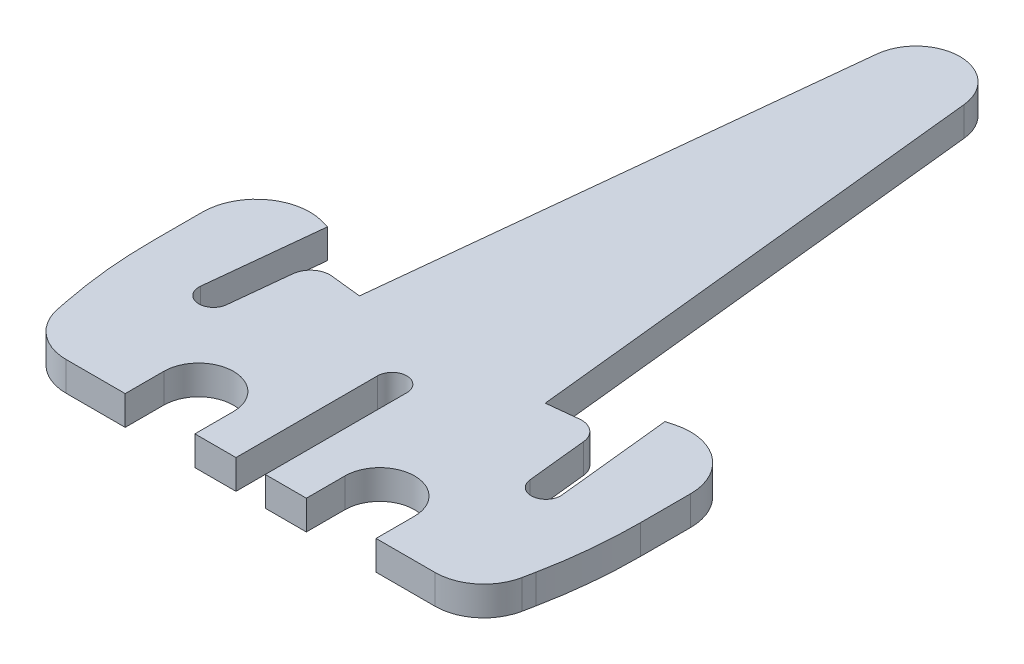
SolidWorks part; units mm, degrees
ref_plane "Front Plane" through (0, 0, 0) normal (0, 0, 1) x (1, 0, 0)
ref_plane "Top Plane" through (0, 0, 0) normal (0, 1, 0) x (1, 0, 0)
ref_plane "Right Plane" through (0, 0, 0) normal (1, 0, 0) x (0, 0, -1)
sketch "Sketch1" plane through (0, 0, 0) normal (0, 1, 0) x (1, 0, 0)
  line L0 (4.4753, 54.1404) -> (9.5172, 6.17)
  line L1 (9.5172, 6.17) -> (12.6862, 6.5137)
  line L2 (14.8909, 4.7344) -> (15.5383, -1.425)
  line L3 (18.5218, -1.1114) -> (17.2833, 10.6723)
  line L4 (17.2833, 10.6723) -> (18.0765, 10.8849)
  line L5 (25, -14.5) -> (25, 5.5723)
  line L6 (25, -14.5) -> (12.85, -14.5) construction
  line L7 (12.85, -14.5) -> (12.85, -10.55)
  line L8 (5.71, -10.55) -> (5.71, -14.5)
  line L9 (5.71, -14.5) -> (1.5, -14.5)
  line L10 (1.5, -14.5) -> (1.5, 0)
  line L11 (-1.5, 0) -> (-1.5, -14.5)
  line L12 (-1.5, -14.5) -> (-5.71, -14.5)
  line L13 (-5.71, -14.5) -> (-5.71, -10.55)
  line L14 (-12.85, -10.55) -> (-12.85, -14.5)
  line L15 (-12.85, -14.5) -> (-25, -14.5) construction
  line L16 (-25, -14.5) -> (-25, 5.5723) construction
  line L17 (-18.0765, 10.8849) -> (-17.2833, 10.6723)
  line L18 (-17.2833, 10.6723) -> (-18.5218, -1.1114)
  line L19 (-15.5383, -1.425) -> (-14.8909, 4.7344)
  line L20 (-12.6862, 6.5137) -> (-9.5172, 6.17)
  line L21 (-9.5172, 6.17) -> (-4.4753, 54.1404)
  line L22 (0, 0) -> (0, 53.67) construction
  line L23 (-24.0358, -9.3022) -> (-23.8017, -10.4772)
  line L24 (24.0358, -9.3022) -> (23.8017, -10.4772)
  line L25 (-25, 5.5723) -> (-25, 0.4696)
  line L26 (25, 0.4696) -> (25, 5.5723)
  line L27 (-18.8981, -14.5) -> (-12.85, -14.5)
  line L28 (12.85, -14.5) -> (18.8981, -14.5)
  arc A0 (-4.4753, 54.1404) -> (4.4753, 54.1404) centre (0, 53.67) cw
  arc A1 (15.5383, -1.425) -> (18.5218, -1.1114) centre (17.0301, -1.2682) ccw
  arc A2 (12.85, -10.55) -> (5.71, -10.55) centre (9.28, -10.55) ccw
  arc A3 (1.5, 0) -> (-1.5, 0) centre (0, 0) ccw
  arc A4 (-5.71, -10.55) -> (-12.85, -10.55) centre (-9.28, -10.55) ccw
  arc A5 (-18.5218, -1.1114) -> (-15.5383, -1.425) centre (-17.0301, -1.2682) ccw
  arc A6 (18.0765, 10.8849) -> (25, 5.5723) centre (19.5, 5.5723) cw
  arc A7 (-25, 5.5723) -> (-18.0765, 10.8849) centre (-19.5, 5.5723) cw
  arc A8 (23.8017, -10.4772) -> (18.8981, -14.5) centre (18.8981, -9.5) cw
  arc A9 (-23.8017, -10.4772) -> (-18.8981, -14.5) centre (-18.8981, -9.5) ccw
  arc A10 (24.0358, -9.3022) -> (25, 0.4696) centre (-25, 0.4696) ccw
  arc A11 (-24.0358, -9.3022) -> (-25, 0.4696) centre (25, 0.4696) cw
  arc A12 (12.6862, 6.5137) -> (14.8909, 4.7344) centre (12.9019, 4.5253) cw
  arc A13 (-14.8909, 4.7344) -> (-12.6862, 6.5137) centre (-12.9019, 4.5253) cw
  point P15 (17.1869, -2.76)
  point P32 (0, 58.17)
  point P35 (0, 1.5)
  point P36 (9.28, -6.98)
  point P43 (23, -14.5)
  point P46 (-23, -14.5)
  point P52 (25, 12.74)
  point P56 (25, -4.4639)
  point P59 (-25, -4.4639)
  point P62 (14.6812, 6.73)
  point P65 (-14.6812, 6.73)
  dimension "D1" = 4.5
  dimension "D6" = 1.5
  dimension "D8" = 3.57
  dimension "D14" = 60.93
  dimension "D12" = 10.6723
  dimension "D15" = 5.5
  dimension "D17" = 5
  dimension "D18" = 50
  dimension "D19" = 2
  dimension "D2" = 12
  dimension "D3" = 6
  dimension "D4" = 72.67
  dimension "D5" = 50
  dimension "D7" = 16
  dimension "D9" = 7.52
  dimension "11.42" = 11.42
  dimension "D10" = 52
  dimension "D11" = 51.44
  dimension "D13" = 81
  dimension "45.43" = 45.43
  dimension "D16" = 2
extrude "Boss-Extrude1" add sketch "Sketch1" along normal blind 3 contours A11 L23 A9 L27 L14 A4 L13 L12 L11 A3 L10 L9 L8 A2 L7 L28 A8 L24 A10 L5 A6 L4 L3 A1 L2 L1 L0 A0 L21 L20 L19 A5 L18 L17 A7 L25
